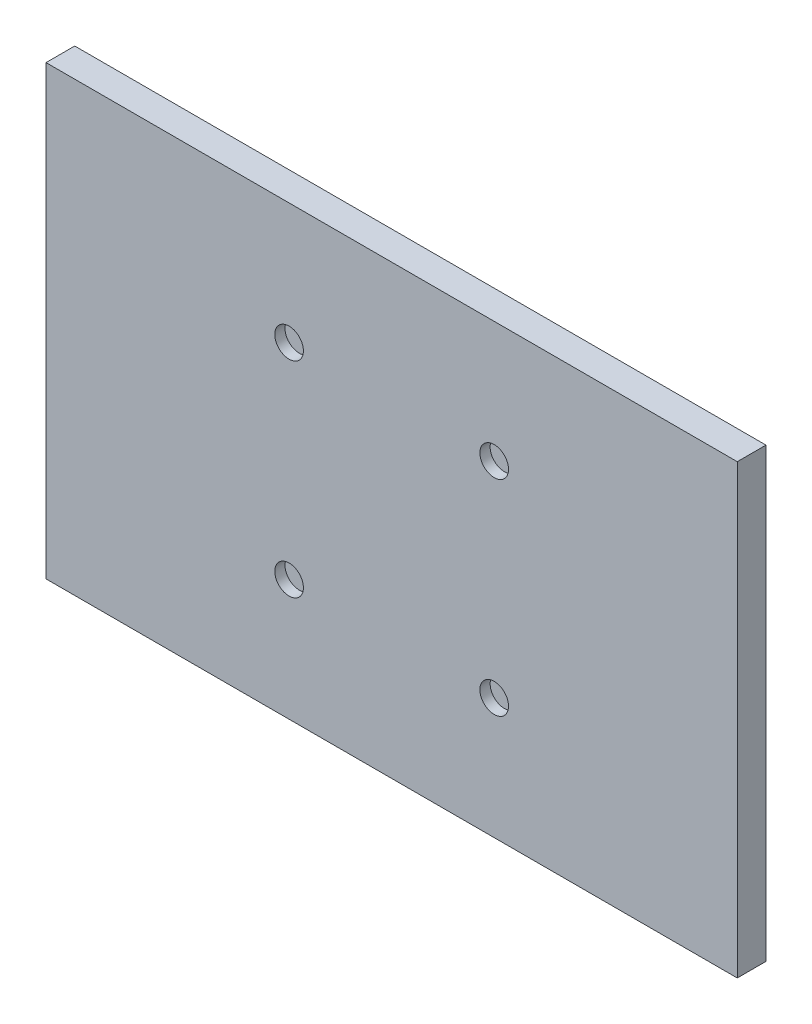
SolidWorks part; units mm, degrees
ref_plane "Front Plane" through (0, 0, 0) normal (0, 0, 1) x (1, 0, 0)
ref_plane "Top Plane" through (0, 0, 0) normal (0, 1, 0) x (1, 0, 0)
ref_plane "Right Plane" through (0, 0, 0) normal (1, 0, 0) x (0, 0, -1)
sketch "Sketch1" plane through (0, 0, 0) normal (0, 0, 1) x (-1, 0, 0)
  line L0 (-84.25, 38.7195) -> (-84.25, -70.2805)
  line L1 (-85, 39.4695) -> (85, 39.4695)
  line L2 (-85, 39.4695) -> (-85, -71.0305)
  line L3 (-85, -71.0305) -> (85, -71.0305)
  line L4 (85, 39.4695) -> (85, -71.0305)
  line L5 (-84.25, -70.2805) -> (84.25, -70.2805)
  line L6 (84.25, 38.7195) -> (84.25, -70.2805)
  line L7 (-84.25, 38.7195) -> (84.25, 38.7195)
  dimension "D2" = 170
  dimension "D3" = 109
  dimension "D1" = 0.75
extrude "Boss-Extrude1" add sketch "Sketch1" along normal blind 7 contours L0 L5 L6 L7
sketch "Sketch2" plane through (0, 0, 7) normal (0, 0, 1) x (1, 0, 0)
  line L1 (-25, -9.2195) -> (25, -9.2195)
  line L2 (-25, -9.2195) -> (-25, 40.7805)
  line L3 (-25, 40.7805) -> (25, 40.7805)
  line L4 (25, -9.2195) -> (25, 40.7805)
  line L5 (-25, -9.2195) -> (25, 40.7805) construction
  line L6 (-25, 40.7805) -> (25, -9.2195) construction
  line L7 (84.25, -38.7195) -> (-84.25, -38.7195) construction
  circle A0 centre (25, 40.7805) radius 3.4934
  circle A1 centre (-25, 40.7805) radius 3.4934
  circle A2 centre (-25, -9.2195) radius 3.4934
  circle A3 centre (25, -9.2195) radius 3.4934
  point P0 (0, 15.7805)
  dimension "D5" = 6.9869
  dimension "D1" = 50
  dimension "D2" = 50
  dimension "D3" = 0
  dimension "D4" = 54.5
  dimension "D6" = 2
  dimension "D7" = 2
extrude "Cut-Extrude1" cut sketch "Sketch2" against normal blind 2.5 contours A0 | A1 | A2 | A3
ref_plane "Plane1" through (0, 0, 3.5) normal (0, 0, 1) x (1, 0, 0)
mirror "Mirror1" about plane through (0, 0, 3.5) normal (0, 0, 1) of "Cut-Extrude1"
